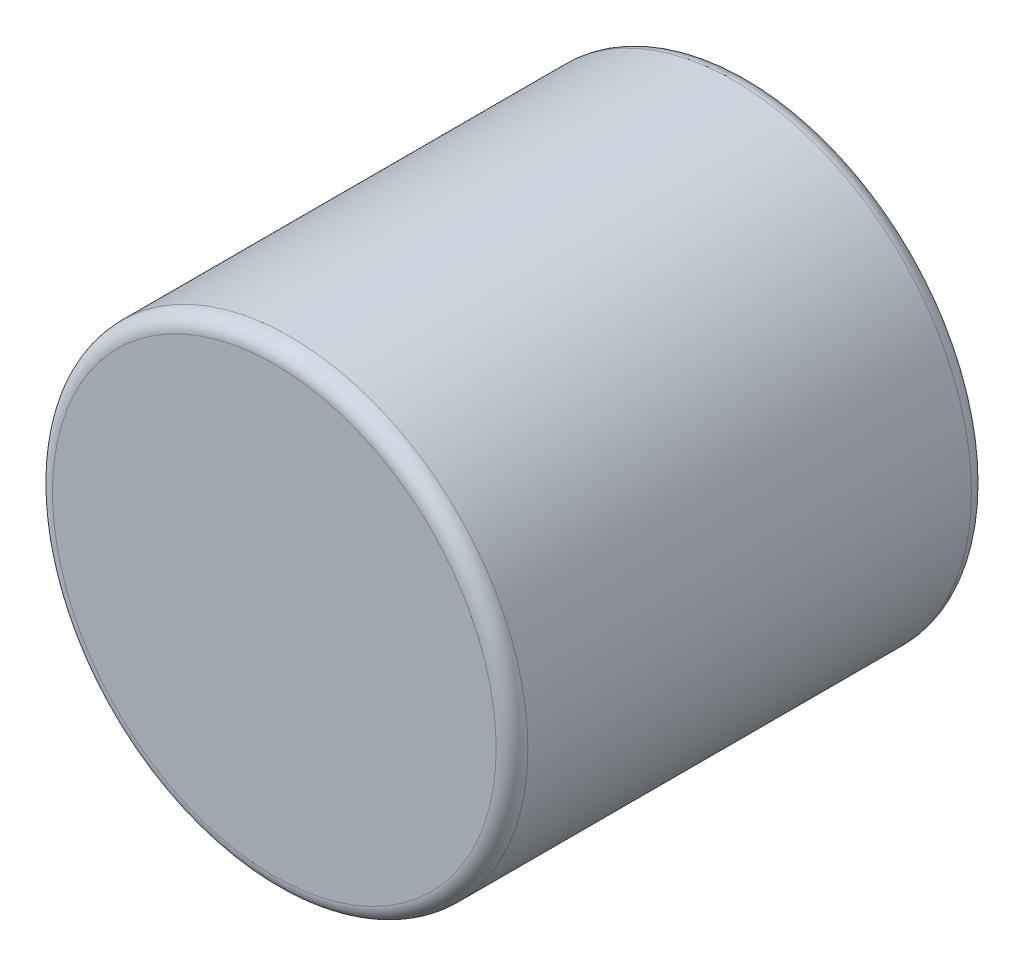
SolidWorks part; units mm, degrees
ref_plane "前视基准面" through (0, 0, 0) normal (0, 0, 1) x (1, 0, 0)
ref_plane "上视基准面" through (0, 0, 0) normal (0, 1, 0) x (1, 0, 0)
ref_plane "右视基准面" through (0, 0, 0) normal (1, 0, 0) x (0, 0, -1)
sketch "草图1" plane through (0, 0, 0) normal (0, 0, 1) x (1, 0, 0)
  circle A0 centre (0, 0) radius 15
  dimension "D1" = 30
extrude "凸台-拉伸1" add sketch "草图1" along normal blind 30
fillet "圆角1" radius 1 2 edges at (15, 0, 0) (15, 0, 30)
sketch "草图2" plane through (0, 0, 0) normal (0, 1, 0) x (1, 0, 0)
  line L0 (0, 2.7788) -> (0, -5.1259) construction
  line L1 (0, 0) -> (3, 0)
  line L2 (14, 0) -> (-14, 0) construction
  line L4 (0, -1.5) -> (0, 0)
  arc A0 (3, 0) -> (2, -1.4142) centre (1.5, 0) cw
  arc A1 (2, -1.4142) -> (1, -2.5) centre (0.5395, -1.0725) cw
  arc A2 (1, -2.5) -> (0, -1.5) centre (0, -2.5) ccw
  dimension "D1" = 1
  dimension "D3" = 1.5
  dimension "D5" = 1.5
  dimension "D2" = 2.5
  dimension "D4" = 3
  dimension "D6" = 2
revolve "切除-旋转1" cut sketch "草图2" angle 360 about L0
